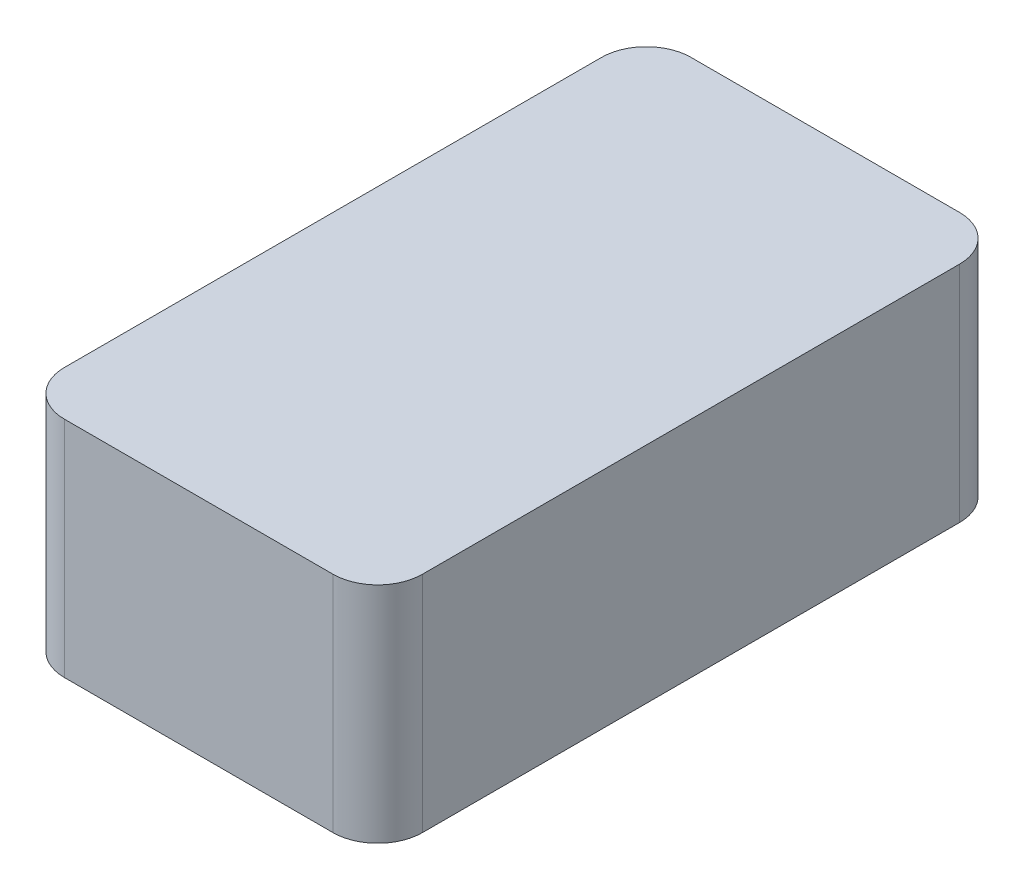
SolidWorks part; units mm, degrees
material "Lipo"
ref_plane "前基準面" through (0, 0, 0) normal (0, 0, 1) x (1, 0, 0)
ref_plane "上基準面" through (0, 0, 0) normal (0, 1, 0) x (1, 0, 0)
ref_plane "右基準面" through (0, 0, 0) normal (1, 0, 0) x (0, 0, -1)
sketch "草圖1" plane through (0, 0, 0) normal (0, 1, 0) x (1, 0, 0)
  line L1 (-40, 70) -> (40, 70)
  line L2 (-40, 70) -> (-40, -70)
  line L3 (-40, -70) -> (40, -70)
  line L4 (40, 70) -> (40, -70)
  line L5 (-40, 70) -> (40, -70) construction
  line L6 (-40, -70) -> (40, 70) construction
  point P0 (0, 0)
  dimension "D1" = 80
  dimension "D2" = 140
extrude "填料-伸長1" add sketch "草圖1" along normal blind 50
fillet "圓角1" radius 10 4 edges at (-40, 25, -70) (40, 25, -70) (40, 25, 70) (-40, 25, 70)
sketch "草圖2" plane through (0, 0, 0) normal (0, -1, 0) x (1, 0, 0)
  line L0 (-40, 0) -> (40, 0)
  line L1 (-40, -60) -> (-40, 60) construction
  line L2 (40, 60) -> (40, -60) construction
